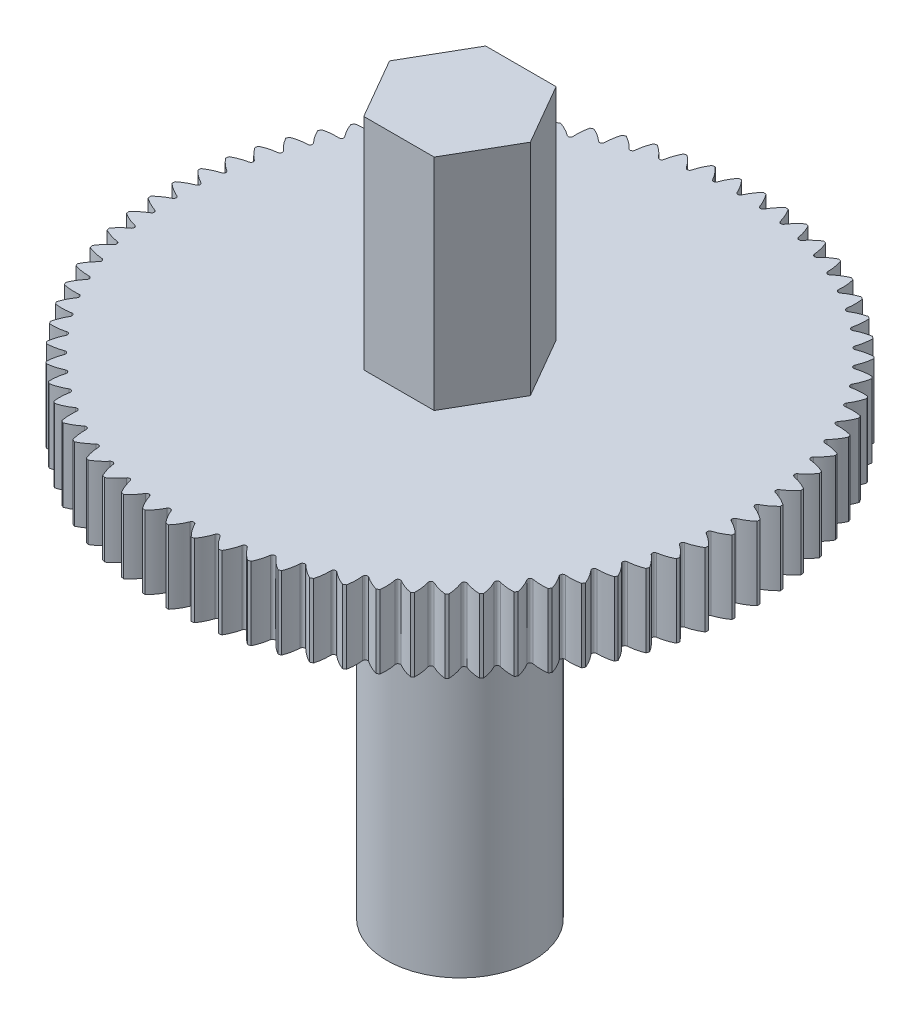
SolidWorks part; units mm, degrees
ref_plane "Ön Düzlem" through (0, 0, 0) normal (0, 0, 1) x (1, 0, 0)
ref_plane "Üst Düzlem" through (0, 0, 0) normal (0, 1, 0) x (1, 0, 0)
ref_plane "Sağ Düzlem" through (0, 0, 0) normal (1, 0, 0) x (0, 0, -1)
sketch "Çizim1" plane through (0, 0, 0) normal (0, 0, 1) x (1, 0, 0)
  line L0 (0, 0) -> (0, 29)
  line L1 (0, 29) -> (3, 29)
  line L2 (3, 29) -> (3, 20)
  line L3 (3, 20) -> (12, 20)
  line L4 (12, 20) -> (12, 17)
  line L5 (12, 17) -> (3, 17)
  line L6 (3, 17) -> (3, 0)
  line L7 (3, 0) -> (0, 0)
  dimension "D1" = 3
  dimension "D2" = 29
  dimension "D3" = 3
  dimension "D4" = 9
  dimension "D5" = 17
revolve "Döndür1" add sketch "Çizim1" angle 360 about L0
sketch "Çizim2" plane through (0, 20, 0) normal (0, 1, 0) x (1, 0, 0)
  line L0 (0, 0) -> (0, 12) construction
  line L1 (0.45, 12) -> (-0.45, 12)
  line L2 (1.4526, 11.9203) -> (0.5557, 11.9956)
  line L3 (2.4449, 11.7569) -> (1.5575, 11.907)
  line L4 (3.4201, 11.5111) -> (2.5484, 11.7349)
  line L5 (4.3714, 11.1845) -> (3.5214, 11.4805)
  line L6 (5.2919, 10.7795) -> (4.4697, 11.1456)
  line L7 (6.1754, 10.2989) -> (5.3867, 10.7325)
  line L8 (7.0155, 9.746) -> (6.2659, 10.2441)
  line L9 (7.8064, 9.1248) -> (7.1011, 9.6838)
  line L10 (8.5426, 8.4396) -> (7.8865, 9.0557)
  line L11 (9.2188, 7.6952) -> (8.6166, 8.364)
  line L12 (9.8304, 6.8968) -> (9.2863, 7.6136)
  line L13 (10.3731, 6.05) -> (9.8908, 6.8099)
  line L14 (10.8429, 5.1608) -> (10.426, 5.9583)
  line L15 (11.2367, 4.2353) -> (10.888, 5.065)
  line L16 (11.5517, 3.2802) -> (11.2736, 4.1362)
  line L17 (11.7857, 2.3021) -> (11.5802, 3.1783)
  line L18 (11.937, 1.3078) -> (11.8055, 2.1982)
  line L19 (12.0046, 0.3044) -> (11.9481, 1.2026)
  line L20 (11.9879, -0.7012) -> (12.0068, 0.1986)
  line L21 (11.8872, -1.7019) -> (11.9813, -0.8068)
  line L22 (11.7031, -2.6906) -> (11.8718, -1.8065)
  line L23 (11.4369, -3.6605) -> (11.679, -2.7936)
  line L24 (11.0905, -4.6046) -> (11.4042, -3.7611)
  line L25 (10.6663, -5.5165) -> (11.0495, -4.7022)
  line L26 (10.1673, -6.3897) -> (10.6173, -5.6103)
  line L27 (9.597, -7.2181) -> (10.1106, -6.479)
  line L28 (8.9593, -7.9958) -> (9.533, -7.3024)
  line L29 (8.2588, -8.7175) -> (8.8885, -8.0744)
  line L30 (7.5004, -9.378) -> (8.1817, -8.7899)
  line L31 (6.6894, -9.9727) -> (7.4175, -9.4437)
  line L32 (5.8314, -10.4975) -> (6.6012, -10.0313)
  line L33 (4.9326, -10.9486) -> (5.7387, -10.5485)
  line L34 (3.9991, -11.323) -> (4.8359, -10.9917)
  line L35 (3.0376, -11.6179) -> (3.8992, -11.3578)
  line L36 (2.0548, -11.8313) -> (2.9351, -11.6442)
  line L37 (1.0575, -11.9618) -> (1.9505, -11.849)
  line L38 (0.0529, -12.0083) -> (0.9521, -11.9706)
  line L39 (-0.9521, -11.9706) -> (-0.0529, -12.0083)
  line L40 (-1.9505, -11.849) -> (-1.0575, -11.9618)
  line L41 (-2.9351, -11.6442) -> (-2.0548, -11.8313)
  line L42 (-3.8992, -11.3578) -> (-3.0376, -11.6179)
  line L43 (-4.8359, -10.9917) -> (-3.9991, -11.323)
  line L44 (-5.7387, -10.5485) -> (-4.9326, -10.9486)
  line L45 (-6.6012, -10.0313) -> (-5.8314, -10.4975)
  line L46 (-7.4175, -9.4437) -> (-6.6894, -9.9727)
  line L47 (-8.1817, -8.7899) -> (-7.5004, -9.378)
  line L48 (-8.8885, -8.0744) -> (-8.2588, -8.7175)
  line L49 (-9.533, -7.3024) -> (-8.9593, -7.9958)
  line L50 (-10.1106, -6.479) -> (-9.597, -7.2181)
  line L51 (-10.6173, -5.6103) -> (-10.1673, -6.3897)
  line L52 (-11.0495, -4.7022) -> (-10.6663, -5.5165)
  line L53 (-11.4042, -3.7611) -> (-11.0905, -4.6046)
  line L54 (-11.679, -2.7936) -> (-11.4369, -3.6605)
  line L55 (-11.8718, -1.8065) -> (-11.7031, -2.6906)
  line L56 (-11.9813, -0.8068) -> (-11.8872, -1.7019)
  line L57 (-12.0068, 0.1986) -> (-11.9879, -0.7012)
  line L58 (-11.9481, 1.2026) -> (-12.0046, 0.3044)
  line L59 (-11.8055, 2.1982) -> (-11.937, 1.3078)
  line L60 (-11.5802, 3.1783) -> (-11.7857, 2.3021)
  line L61 (-11.2736, 4.1362) -> (-11.5517, 3.2802)
  line L62 (-10.888, 5.065) -> (-11.2367, 4.2353)
  line L63 (-10.426, 5.9583) -> (-10.8429, 5.1608)
  line L64 (-9.8908, 6.8099) -> (-10.3731, 6.05)
  line L65 (-9.2863, 7.6136) -> (-9.8304, 6.8968)
  line L66 (-8.6166, 8.364) -> (-9.2188, 7.6952)
  line L67 (-7.8865, 9.0557) -> (-8.5426, 8.4396)
  line L68 (-7.1011, 9.6838) -> (-7.8064, 9.1248)
  line L69 (-6.2659, 10.2441) -> (-7.0155, 9.746)
  line L70 (-5.3867, 10.7325) -> (-6.1754, 10.2989)
  line L71 (-4.4697, 11.1456) -> (-5.2919, 10.7795)
  line L72 (-3.5214, 11.4805) -> (-4.3714, 11.1845)
  line L73 (-2.5484, 11.7349) -> (-3.4201, 11.5111)
  line L74 (-1.5575, 11.907) -> (-2.4449, 11.7569)
  line L75 (-0.5557, 11.9956) -> (-1.4526, 11.9203)
  circle A0 centre (0, 0) radius 12 construction
  arc A1 (0.45, 12) -> (0.0912, 11.459) centre (1.9153, 10.6388) ccw
  arc A2 (0.0912, 11.459) -> (-0.0912, 11.459) centre (0, 11.5) cw
  arc A3 (-0.45, 12) -> (-0.0912, 11.459) centre (-1.9153, 10.6388) cw
  arc A4 (0.5557, 11.9956) -> (0.868, 11.4264) centre (-1.0183, 10.7617) cw
  arc A5 (1.0497, 11.4112) -> (0.868, 11.4264) centre (0.9623, 11.4597) cw
  arc A6 (1.4526, 11.9203) -> (1.0497, 11.4112) centre (2.7988, 10.4412) ccw
  arc A7 (1.5575, 11.907) -> (1.8211, 11.3137) centre (-0.1142, 10.8092) cw
  arc A8 (2.0009, 11.2833) -> (1.8211, 11.3137) centre (1.9178, 11.339) cw
  arc A9 (2.4449, 11.7569) -> (2.0009, 11.2833) centre (3.6627, 10.1704) ccw
  arc A10 (2.5484, 11.7349) -> (2.7614, 11.1217) centre (0.7907, 10.7808) cw
  arc A11 (2.9381, 11.0763) -> (2.7614, 11.1217) centre (2.8599, 11.1387) cw
  arc A12 (3.4201, 11.5111) -> (2.9381, 11.0763) centre (4.5008, 9.8282) ccw
  arc A13 (3.5214, 11.4805) -> (3.6823, 10.8516) centre (1.69, 10.6769) cw
  arc A14 (3.8546, 10.7916) -> (3.6823, 10.8516) centre (3.782, 10.8603) cw
  arc A15 (4.3714, 11.1845) -> (3.8546, 10.7916) centre (5.3075, 9.4171) ccw
  arc A16 (4.4697, 11.1456) -> (4.5775, 10.5054) centre (2.5775, 10.498) cw
  arc A17 (4.7441, 10.4312) -> (4.5775, 10.5054) centre (4.6775, 10.5058) cw
  arc A18 (5.2919, 10.7795) -> (4.7441, 10.4312) centre (6.0769, 8.94) ccw
  arc A19 (5.3867, 10.7325) -> (5.4405, 10.0855) centre (3.4469, 10.2455) cw
  arc A20 (5.6003, 9.9977) -> (5.4405, 10.0855) centre (5.5402, 10.0775) cw
  arc A21 (6.1754, 10.2989) -> (5.6003, 9.9977) centre (6.8036, 8.4001) ccw
  arc A22 (6.2659, 10.2441) -> (6.2653, 9.5949) centre (4.2921, 9.9211) cw
  arc A23 (6.4173, 9.494) -> (6.2653, 9.5949) centre (6.364, 9.5786) cw
  arc A24 (7.0155, 9.746) -> (6.4173, 9.494) centre (7.4827, 7.8014) ccw
  arc A25 (7.1011, 9.6838) -> (7.0462, 9.037) centre (5.1073, 9.5272) cw
  arc A26 (7.1892, 8.9237) -> (7.0462, 9.037) centre (7.1432, 9.0125) cw
  arc A27 (7.8064, 9.1248) -> (7.1892, 8.9237) centre (8.1092, 7.1479) ccw
  arc A28 (7.8865, 9.0557) -> (7.7777, 8.4157) centre (5.8866, 9.0664) cw
  arc A29 (7.9107, 8.2908) -> (7.7777, 8.4157) centre (7.8723, 8.3831) cw
  arc A30 (8.5426, 8.4396) -> (7.9107, 8.2908) centre (8.6789, 6.4442) ccw
  arc A31 (8.6166, 8.364) -> (8.4547, 7.7353) centre (6.6246, 8.542) cw
  arc A32 (8.5767, 7.5998) -> (8.4547, 7.7353) centre (8.5462, 7.695) cw
  arc A33 (9.2188, 7.6952) -> (8.5767, 7.5998) centre (9.1877, 5.6954) ccw
  arc A34 (9.2863, 7.6136) -> (9.0723, 7.0007) centre (7.3161, 7.9578) cw
  arc A35 (9.1826, 6.8554) -> (9.0723, 7.0007) centre (9.1601, 6.9529) cw
  arc A36 (9.8304, 6.8968) -> (9.1826, 6.8554) centre (9.6321, 4.9066) ccw
  arc A37 (9.8908, 6.8099) -> (9.6263, 6.217) centre (7.9563, 7.3176) cw
  arc A38 (9.724, 6.063) -> (9.6263, 6.217) centre (9.7098, 6.162) cw
  arc A39 (10.3731, 6.05) -> (9.724, 6.063) centre (10.0089, 4.0834) ccw
  arc A40 (10.426, 5.9583) -> (10.1127, 5.3897) centre (8.5408, 6.6262) cw
  arc A41 (10.1973, 5.2281) -> (10.1127, 5.3897) centre (10.1913, 5.3279) cw
  arc A42 (10.8429, 5.1608) -> (10.1973, 5.2281) centre (10.3154, 3.2316) ccw
  arc A43 (10.888, 5.065) -> (10.5283, 4.5246) centre (9.0653, 5.8883) cw
  arc A44 (10.599, 4.3565) -> (10.5283, 4.5246) centre (10.6014, 4.4564) cw
  arc A45 (11.2367, 4.2353) -> (10.599, 4.3565) centre (10.5497, 2.3571) ccw
  arc A46 (11.2736, 4.1362) -> (10.87, 3.6278) centre (9.5262, 5.1091) cw
  arc A47 (10.9263, 3.4543) -> (10.87, 3.6278) centre (10.9371, 3.5537) cw
  arc A48 (11.5517, 3.2802) -> (10.9263, 3.4543) centre (10.7099, 1.466) ccw
  arc A49 (11.5802, 3.1783) -> (11.1354, 2.7055) centre (9.9203, 4.294) cw
  arc A50 (11.1771, 2.5279) -> (11.1354, 2.7055) centre (11.1962, 2.626) cw
  arc A51 (11.7857, 2.3021) -> (11.1771, 2.5279) centre (10.795, 0.5647) ccw
  arc A52 (11.8055, 2.1982) -> (11.3227, 1.7642) centre (10.2448, 3.4489) cw
  arc A53 (11.3494, 1.5837) -> (11.3227, 1.7642) centre (11.3766, 1.68) cw
  arc A54 (11.937, 1.3078) -> (11.3494, 1.5837) centre (10.8044, -0.3406) ccw
  arc A55 (11.9481, 1.2026) -> (11.4307, 0.8105) centre (10.4975, 2.5795) cw
  arc A56 (11.4421, 0.6285) -> (11.4307, 0.8105) centre (11.4773, 0.7221) cw
  arc A57 (12.0046, 0.3044) -> (11.4421, 0.6285) centre (10.738, -1.2435) ccw
  arc A58 (12.0068, 0.1986) -> (11.4584, -0.1488) centre (10.6765, 1.692) cw
  arc A59 (11.4546, -0.3312) -> (11.4584, -0.1488) centre (11.4975, -0.2408) cw
  arc A60 (11.9879, -0.7012) -> (11.4546, -0.3312) centre (10.5963, -2.1377) ccw
  arc A61 (11.9813, -0.8068) -> (11.4057, -1.1071) centre (10.7807, 0.7927) cw
  arc A62 (11.3867, -1.2885) -> (11.4057, -1.1071) centre (11.437, -1.2021) cw
  arc A63 (11.8872, -1.7019) -> (11.3867, -1.2885) centre (10.3803, -3.0168) ccw
  arc A64 (11.8718, -1.8065) -> (11.2731, -2.0576) centre (10.8092, -0.1122) cw
  arc A65 (11.2389, -2.2368) -> (11.2731, -2.0576) centre (11.2963, -2.1549) cw
  arc A66 (11.7031, -2.6906) -> (11.2389, -2.2368) centre (10.0914, -3.8748) ccw
  arc A67 (11.679, -2.7936) -> (11.0614, -2.9937) centre (10.7619, -1.0163) cw
  arc A68 (11.0123, -3.1694) -> (11.0614, -2.9937) centre (11.0764, -3.0926) cw
  arc A69 (11.4369, -3.6605) -> (11.0123, -3.1694) centre (9.7318, -4.7057) ccw
  arc A70 (11.4042, -3.7611) -> (10.7721, -3.9088) centre (10.6391, -1.9132) cw
  arc A71 (10.7085, -4.0798) -> (10.7721, -3.9088) centre (10.7787, -4.0086) cw
  arc A72 (11.0905, -4.6046) -> (10.7085, -4.0798) centre (9.3039, -5.5035) ccw
  arc A73 (11.0495, -4.7022) -> (10.4072, -4.7965) centre (10.4417, -2.7968) cw
  arc A74 (10.3296, -4.9615) -> (10.4072, -4.7965) centre (10.4055, -4.8965) cw
  arc A75 (10.6663, -5.5165) -> (10.3296, -4.9615) centre (8.8108, -6.2628) ccw
  arc A76 (10.6173, -5.6103) -> (9.9694, -5.6505) centre (10.1711, -3.6607) cw
  arc A77 (9.8782, -5.8085) -> (9.9694, -5.6505) centre (9.9593, -5.75) cw
  arc A78 (10.1673, -6.3897) -> (9.8782, -5.8085) centre (8.2558, -6.9781) ccw
  arc A79 (10.1106, -6.479) -> (9.4616, -6.4649) centre (9.8291, -4.499) cw
  arc A80 (9.3575, -6.6147) -> (9.4616, -6.4649) centre (9.4432, -6.5632) cw
  arc A81 (9.597, -7.2181) -> (9.3575, -6.6147) centre (7.6429, -7.6444) ccw
  arc A82 (9.533, -7.3024) -> (8.8874, -7.234) centre (9.4181, -5.3057) cw
  arc A83 (8.7712, -7.3745) -> (8.8874, -7.234) centre (8.8609, -7.3304) cw
  arc A84 (8.9593, -7.9958) -> (8.7712, -7.3745) centre (6.9765, -8.2571) ccw
  arc A85 (8.8885, -8.0744) -> (8.2509, -7.9523) centre (8.9411, -6.0751) cw
  arc A86 (8.1233, -8.0826) -> (8.2509, -7.9523) centre (8.2164, -8.0461) cw
  arc A87 (8.2588, -8.7175) -> (8.1233, -8.0826) centre (6.2611, -8.812) ccw
  arc A88 (8.1817, -8.7899) -> (7.5566, -8.6148) centre (8.4014, -6.802) cw
  arc A89 (7.4185, -8.734) -> (7.5566, -8.6148) centre (7.5143, -8.7054) cw
  arc A90 (7.5004, -9.378) -> (7.4185, -8.734) centre (5.5017, -9.305) ccw
  arc A91 (7.4175, -9.4437) -> (6.8092, -9.2169) centre (7.8028, -7.4812) cw
  arc A92 (6.6616, -9.3241) -> (6.8092, -9.2169) centre (6.7595, -9.3037) cw
  arc A93 (6.6894, -9.9727) -> (6.6616, -9.3241) centre (4.7038, -9.7327) ccw
  arc A94 (6.6012, -10.0313) -> (6.0141, -9.7544) centre (7.1494, -8.1079) cw
  arc A95 (5.8581, -9.8489) -> (6.0141, -9.7544) centre (5.9573, -9.8367) cw
  arc A96 (5.8314, -10.4975) -> (5.8581, -9.8489) centre (3.8729, -10.0922) ccw
  arc A97 (5.7387, -10.5485) -> (5.1768, -10.2234) centre (6.4459, -8.6777) cw
  arc A98 (5.0134, -10.3045) -> (5.1768, -10.2234) centre (5.1133, -10.3007) cw
  arc A99 (4.9326, -10.9486) -> (5.0134, -10.3045) centre (3.0148, -10.3809) ccw
  arc A100 (4.8359, -10.9917) -> (4.3031, -10.6207) centre (5.6972, -9.1866) cw
  arc A101 (4.1335, -10.6879) -> (4.3031, -10.6207) centre (4.2334, -10.6924) cw
  arc A102 (3.9991, -11.323) -> (4.1335, -10.6879) centre (2.1356, -10.5967) ccw
  arc A103 (3.8992, -11.3578) -> (3.3993, -10.9436) centre (4.9085, -9.6311) cw
  arc A104 (3.2247, -10.9963) -> (3.3993, -10.9436) centre (3.3239, -11.0092) cw
  arc A105 (3.0376, -11.6179) -> (3.2247, -10.9963) centre (1.2414, -10.7383) ccw
  arc A106 (2.9351, -11.6442) -> (2.4717, -11.1896) centre (4.0853, -10.0081) cw
  arc A107 (2.2932, -11.2275) -> (2.4717, -11.1896) centre (2.391, -11.2487) cw
  arc A108 (2.0548, -11.8313) -> (2.2932, -11.2275) centre (0.3385, -10.8045) ccw
  arc A109 (1.9505, -11.849) -> (1.5267, -11.3572) centre (3.2336, -10.3148) cw
  arc A110 (1.3457, -11.3801) -> (1.5267, -11.3572) centre (1.4413, -11.4093) cw
  arc A111 (1.0575, -11.9618) -> (1.3457, -11.3801) centre (-0.5668, -10.7949) ccw
  arc A112 (0.9521, -11.9706) -> (0.571, -11.4451) centre (2.3591, -10.5492) cw
  arc A113 (0.3887, -11.4528) -> (0.571, -11.4451) centre (0.4816, -11.4899) cw
  arc A114 (0.0529, -12.0083) -> (0.3887, -11.4528) centre (-1.4681, -10.7096) ccw
  arc A115 (-0.0529, -12.0083) -> (-0.3887, -11.4528) centre (1.4681, -10.7096) cw
  arc A116 (-0.571, -11.4451) -> (-0.3887, -11.4528) centre (-0.4816, -11.4899) cw
  arc A117 (-0.9521, -11.9706) -> (-0.571, -11.4451) centre (-2.3591, -10.5492) ccw
  arc A118 (-1.0575, -11.9618) -> (-1.3457, -11.3801) centre (0.5668, -10.7949) cw
  arc A119 (-1.5267, -11.3572) -> (-1.3457, -11.3801) centre (-1.4413, -11.4093) cw
  arc A120 (-1.9505, -11.849) -> (-1.5267, -11.3572) centre (-3.2336, -10.3148) ccw
  arc A121 (-2.0548, -11.8313) -> (-2.2932, -11.2275) centre (-0.3385, -10.8045) cw
  arc A122 (-2.4717, -11.1896) -> (-2.2932, -11.2275) centre (-2.391, -11.2487) cw
  arc A123 (-2.9351, -11.6442) -> (-2.4717, -11.1896) centre (-4.0853, -10.0081) ccw
  arc A124 (-3.0376, -11.6179) -> (-3.2247, -10.9963) centre (-1.2414, -10.7383) cw
  arc A125 (-3.3993, -10.9436) -> (-3.2247, -10.9963) centre (-3.3239, -11.0092) cw
  arc A126 (-3.8992, -11.3578) -> (-3.3993, -10.9436) centre (-4.9085, -9.6311) ccw
  arc A127 (-3.9991, -11.323) -> (-4.1335, -10.6879) centre (-2.1356, -10.5967) cw
  arc A128 (-4.3031, -10.6207) -> (-4.1335, -10.6879) centre (-4.2334, -10.6924) cw
  arc A129 (-4.8359, -10.9917) -> (-4.3031, -10.6207) centre (-5.6972, -9.1866) ccw
  arc A130 (-4.9326, -10.9486) -> (-5.0134, -10.3045) centre (-3.0148, -10.3809) cw
  arc A131 (-5.1768, -10.2234) -> (-5.0134, -10.3045) centre (-5.1133, -10.3007) cw
  arc A132 (-5.7387, -10.5485) -> (-5.1768, -10.2234) centre (-6.4459, -8.6777) ccw
  arc A133 (-5.8314, -10.4975) -> (-5.8581, -9.8489) centre (-3.8729, -10.0922) cw
  arc A134 (-6.0141, -9.7544) -> (-5.8581, -9.8489) centre (-5.9573, -9.8367) cw
  arc A135 (-6.6012, -10.0313) -> (-6.0141, -9.7544) centre (-7.1494, -8.1079) ccw
  arc A136 (-6.6894, -9.9727) -> (-6.6616, -9.3241) centre (-4.7038, -9.7327) cw
  arc A137 (-6.8092, -9.2169) -> (-6.6616, -9.3241) centre (-6.7595, -9.3037) cw
  arc A138 (-7.4175, -9.4437) -> (-6.8092, -9.2169) centre (-7.8028, -7.4812) ccw
  arc A139 (-7.5004, -9.378) -> (-7.4185, -8.734) centre (-5.5017, -9.305) cw
  arc A140 (-7.5566, -8.6148) -> (-7.4185, -8.734) centre (-7.5143, -8.7054) cw
  arc A141 (-8.1817, -8.7899) -> (-7.5566, -8.6148) centre (-8.4014, -6.802) ccw
  arc A142 (-8.2588, -8.7175) -> (-8.1233, -8.0826) centre (-6.2611, -8.812) cw
  arc A143 (-8.2509, -7.9523) -> (-8.1233, -8.0826) centre (-8.2164, -8.0461) cw
  arc A144 (-8.8885, -8.0744) -> (-8.2509, -7.9523) centre (-8.9411, -6.0751) ccw
  arc A145 (-8.9593, -7.9958) -> (-8.7712, -7.3745) centre (-6.9765, -8.2571) cw
  arc A146 (-8.8874, -7.234) -> (-8.7712, -7.3745) centre (-8.8609, -7.3304) cw
  arc A147 (-9.533, -7.3024) -> (-8.8874, -7.234) centre (-9.4181, -5.3057) ccw
  arc A148 (-9.597, -7.2181) -> (-9.3575, -6.6147) centre (-7.6429, -7.6444) cw
  arc A149 (-9.4616, -6.4649) -> (-9.3575, -6.6147) centre (-9.4432, -6.5632) cw
  arc A150 (-10.1106, -6.479) -> (-9.4616, -6.4649) centre (-9.8291, -4.499) ccw
  arc A151 (-10.1673, -6.3897) -> (-9.8782, -5.8085) centre (-8.2558, -6.9781) cw
  arc A152 (-9.9694, -5.6505) -> (-9.8782, -5.8085) centre (-9.9593, -5.75) cw
  arc A153 (-10.6173, -5.6103) -> (-9.9694, -5.6505) centre (-10.1711, -3.6607) ccw
  arc A154 (-10.6663, -5.5165) -> (-10.3296, -4.9615) centre (-8.8108, -6.2628) cw
  arc A155 (-10.4072, -4.7965) -> (-10.3296, -4.9615) centre (-10.4055, -4.8965) cw
  arc A156 (-11.0495, -4.7022) -> (-10.4072, -4.7965) centre (-10.4417, -2.7968) ccw
  arc A157 (-11.0905, -4.6046) -> (-10.7085, -4.0798) centre (-9.3039, -5.5035) cw
  arc A158 (-10.7721, -3.9088) -> (-10.7085, -4.0798) centre (-10.7787, -4.0086) cw
  arc A159 (-11.4042, -3.7611) -> (-10.7721, -3.9088) centre (-10.6391, -1.9132) ccw
  arc A160 (-11.4369, -3.6605) -> (-11.0123, -3.1694) centre (-9.7318, -4.7057) cw
  arc A161 (-11.0614, -2.9937) -> (-11.0123, -3.1694) centre (-11.0764, -3.0926) cw
  arc A162 (-11.679, -2.7936) -> (-11.0614, -2.9937) centre (-10.7619, -1.0163) ccw
  arc A163 (-11.7031, -2.6906) -> (-11.2389, -2.2368) centre (-10.0914, -3.8748) cw
  arc A164 (-11.2731, -2.0576) -> (-11.2389, -2.2368) centre (-11.2963, -2.1549) cw
  arc A165 (-11.8718, -1.8065) -> (-11.2731, -2.0576) centre (-10.8092, -0.1122) ccw
  arc A166 (-11.8872, -1.7019) -> (-11.3867, -1.2885) centre (-10.3803, -3.0168) cw
  arc A167 (-11.4057, -1.1071) -> (-11.3867, -1.2885) centre (-11.437, -1.2021) cw
  arc A168 (-11.9813, -0.8068) -> (-11.4057, -1.1071) centre (-10.7807, 0.7927) ccw
  arc A169 (-11.9879, -0.7012) -> (-11.4546, -0.3312) centre (-10.5963, -2.1377) cw
  arc A170 (-11.4584, -0.1488) -> (-11.4546, -0.3312) centre (-11.4975, -0.2408) cw
  arc A171 (-12.0068, 0.1986) -> (-11.4584, -0.1488) centre (-10.6765, 1.692) ccw
  arc A172 (-12.0046, 0.3044) -> (-11.4421, 0.6285) centre (-10.738, -1.2435) cw
  arc A173 (-11.4307, 0.8105) -> (-11.4421, 0.6285) centre (-11.4773, 0.7221) cw
  arc A174 (-11.9481, 1.2026) -> (-11.4307, 0.8105) centre (-10.4975, 2.5795) ccw
  arc A175 (-11.937, 1.3078) -> (-11.3494, 1.5837) centre (-10.8044, -0.3406) cw
  arc A176 (-11.3227, 1.7642) -> (-11.3494, 1.5837) centre (-11.3766, 1.68) cw
  arc A177 (-11.8055, 2.1982) -> (-11.3227, 1.7642) centre (-10.2448, 3.4489) ccw
  arc A178 (-11.7857, 2.3021) -> (-11.1771, 2.5279) centre (-10.795, 0.5647) cw
  arc A179 (-11.1354, 2.7055) -> (-11.1771, 2.5279) centre (-11.1962, 2.626) cw
  arc A180 (-11.5802, 3.1783) -> (-11.1354, 2.7055) centre (-9.9203, 4.294) ccw
  arc A181 (-11.5517, 3.2802) -> (-10.9263, 3.4543) centre (-10.7099, 1.466) cw
  arc A182 (-10.87, 3.6278) -> (-10.9263, 3.4543) centre (-10.9371, 3.5537) cw
  arc A183 (-11.2736, 4.1362) -> (-10.87, 3.6278) centre (-9.5262, 5.1091) ccw
  arc A184 (-11.2367, 4.2353) -> (-10.599, 4.3565) centre (-10.5497, 2.3571) cw
  arc A185 (-10.5283, 4.5246) -> (-10.599, 4.3565) centre (-10.6014, 4.4564) cw
  arc A186 (-10.888, 5.065) -> (-10.5283, 4.5246) centre (-9.0653, 5.8883) ccw
  arc A187 (-10.8429, 5.1608) -> (-10.1973, 5.2281) centre (-10.3154, 3.2316) cw
  arc A188 (-10.1127, 5.3897) -> (-10.1973, 5.2281) centre (-10.1913, 5.3279) cw
  arc A189 (-10.426, 5.9583) -> (-10.1127, 5.3897) centre (-8.5408, 6.6262) ccw
  arc A190 (-10.3731, 6.05) -> (-9.724, 6.063) centre (-10.0089, 4.0834) cw
  arc A191 (-9.6263, 6.217) -> (-9.724, 6.063) centre (-9.7098, 6.162) cw
  arc A192 (-9.8908, 6.8099) -> (-9.6263, 6.217) centre (-7.9563, 7.3176) ccw
  arc A193 (-9.8304, 6.8968) -> (-9.1826, 6.8554) centre (-9.6321, 4.9066) cw
  arc A194 (-9.0723, 7.0007) -> (-9.1826, 6.8554) centre (-9.1601, 6.9529) cw
  arc A195 (-9.2863, 7.6136) -> (-9.0723, 7.0007) centre (-7.3161, 7.9578) ccw
  arc A196 (-9.2188, 7.6952) -> (-8.5767, 7.5998) centre (-9.1877, 5.6954) cw
  arc A197 (-8.4547, 7.7353) -> (-8.5767, 7.5998) centre (-8.5462, 7.695) cw
  arc A198 (-8.6166, 8.364) -> (-8.4547, 7.7353) centre (-6.6246, 8.542) ccw
  arc A199 (-8.5426, 8.4396) -> (-7.9107, 8.2908) centre (-8.6789, 6.4442) cw
  arc A200 (-7.7777, 8.4157) -> (-7.9107, 8.2908) centre (-7.8723, 8.3831) cw
  arc A201 (-7.8865, 9.0557) -> (-7.7777, 8.4157) centre (-5.8866, 9.0664) ccw
  arc A202 (-7.8064, 9.1248) -> (-7.1892, 8.9237) centre (-8.1092, 7.1479) cw
  arc A203 (-7.0462, 9.037) -> (-7.1892, 8.9237) centre (-7.1432, 9.0125) cw
  arc A204 (-7.1011, 9.6838) -> (-7.0462, 9.037) centre (-5.1073, 9.5272) ccw
  arc A205 (-7.0155, 9.746) -> (-6.4173, 9.494) centre (-7.4827, 7.8014) cw
  arc A206 (-6.2653, 9.5949) -> (-6.4173, 9.494) centre (-6.364, 9.5786) cw
  arc A207 (-6.2659, 10.2441) -> (-6.2653, 9.5949) centre (-4.2921, 9.9211) ccw
  arc A208 (-6.1754, 10.2989) -> (-5.6003, 9.9977) centre (-6.8036, 8.4001) cw
  arc A209 (-5.4405, 10.0855) -> (-5.6003, 9.9977) centre (-5.5402, 10.0775) cw
  arc A210 (-5.3867, 10.7325) -> (-5.4405, 10.0855) centre (-3.4469, 10.2455) ccw
  arc A211 (-5.2919, 10.7795) -> (-4.7441, 10.4312) centre (-6.0769, 8.94) cw
  arc A212 (-4.5775, 10.5054) -> (-4.7441, 10.4312) centre (-4.6775, 10.5058) cw
  arc A213 (-4.4697, 11.1456) -> (-4.5775, 10.5054) centre (-2.5775, 10.498) ccw
  arc A214 (-4.3714, 11.1845) -> (-3.8546, 10.7916) centre (-5.3075, 9.4171) cw
  arc A215 (-3.6823, 10.8516) -> (-3.8546, 10.7916) centre (-3.782, 10.8603) cw
  arc A216 (-3.5214, 11.4805) -> (-3.6823, 10.8516) centre (-1.69, 10.6769) ccw
  arc A217 (-3.4201, 11.5111) -> (-2.9381, 11.0763) centre (-4.5008, 9.8282) cw
  arc A218 (-2.7614, 11.1217) -> (-2.9381, 11.0763) centre (-2.8599, 11.1387) cw
  arc A219 (-2.5484, 11.7349) -> (-2.7614, 11.1217) centre (-0.7907, 10.7808) ccw
  arc A220 (-2.4449, 11.7569) -> (-2.0009, 11.2833) centre (-3.6627, 10.1704) cw
  arc A221 (-1.8211, 11.3137) -> (-2.0009, 11.2833) centre (-1.9178, 11.339) cw
  arc A222 (-1.5575, 11.907) -> (-1.8211, 11.3137) centre (0.1142, 10.8092) ccw
  arc A223 (-1.4526, 11.9203) -> (-1.0497, 11.4112) centre (-2.7988, 10.4412) cw
  arc A224 (-0.868, 11.4264) -> (-1.0497, 11.4112) centre (-0.9623, 11.4597) cw
  arc A225 (-0.5557, 11.9956) -> (-0.868, 11.4264) centre (1.0183, 10.7617) ccw
  dimension "D2" = 0.1
  dimension "D3" = 2
  dimension "D1" = 0.9
  dimension "D4" = 0.5
  dimension "D5" = 75
extrude "Kes-Ekstrüzyon1" cut sketch "Çizim2" against normal blind 6
sketch "Çizim3" plane through (0, 29, 0) normal (0, 1, 0) x (1, 0, 0)
  line L7 (1.4434, -2.5) -> (2.8868, 0)
  line L8 (2.8868, 0) -> (1.4434, 2.5)
  line L9 (1.4434, 2.5) -> (-1.4434, 2.5)
  line L10 (-1.4434, 2.5) -> (-2.8868, 0)
  line L11 (-2.8868, 0) -> (-1.4434, -2.5)
  line L12 (-1.4434, -2.5) -> (1.4434, -2.5)
  circle A0 centre (0, 0) radius 2.5 construction
  circle A1 centre (0, 0) radius 3 construction
  circle A2 centre (0, 0) radius 3 construction
  circle A3 centre (0, 0) radius 3
  circle A4 centre (0, 0) radius 3
  circle M10 centre (0, 0) radius 3
  dimension "D1" = 5
extrude "Kes-Ekstrüzyon2" cut sketch "Çizim3" against normal up to surface (9 mm away) contours L12 L11 L10 L9 L8 L7 M10 up to face at (0, 20, 0)
